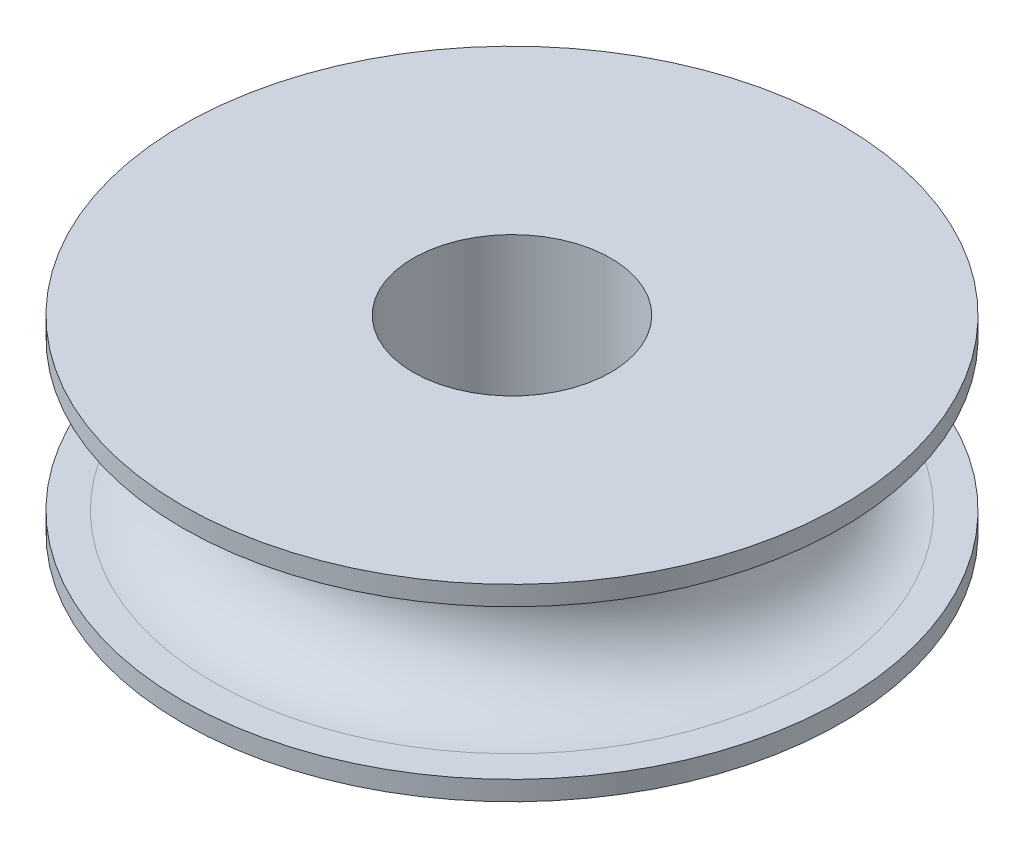
SolidWorks part; units mm, degrees
material "ABS PC"
ref_plane "Front Plane" through (0, 0, 0) normal (0, 0, 1) x (1, 0, 0)
ref_plane "Top Plane" through (0, 0, 0) normal (0, 1, 0) x (1, 0, 0)
ref_plane "Right Plane" through (0, 0, 0) normal (1, 0, 0) x (0, 0, -1)
sketch "Sketch1" plane through (0, 0, 0) normal (0, 0, 1) x (1, 0, 0)
  line L0 (0, 5.8882) -> (0, -5.8882) construction
  line L1 (-10.5, -3) -> (-5, -3)
  line L2 (-10.5, -3) -> (-10.5, -2.3812)
  line L3 (-10.5, -2.3812) -> (-9.5, -2.3813)
  line L4 (-9.5, 2.3812) -> (-10.5, 2.3813)
  line L5 (-10.5, 2.3813) -> (-10.5, 3)
  line L6 (-10.5, 3) -> (0, 3)
  line L7 (0, -5.5) -> (0, 3)
  line L12 (-5, -3) -> (-5, -5.5)
  line L13 (-5, -5.5) -> (0, -5.5)
  arc A0 (-9.5, 2.3812) -> (-9.5, -2.3813) centre (-9.5, 0) cw
  dimension "D3" = 9.5
  dimension "D5" = 2.3813
  dimension "D1" = 5.5
  dimension "D2" = 6
  dimension "D4" = 5
  dimension "D6" = 10.5
  dimension "D7" = 3
revolve "Revolve1" add sketch "Sketch1" angle 360 about L0
sketch "Sketch2" plane through (0, 3, 0) normal (0, 1, 0) x (1, 0, 0)
  circle A0 centre (0, 0) radius 3.15
  dimension "D1" = 6.3
extrude "Cut-Extrude1" cut sketch "Sketch2" against normal through all
ref_plane "Plane1" through (5, 0, 0) normal (1, 0, 0) x (0, 0, -1)
hole_wizard "M2x0.4 Tapped Hole2" positions "Sketch7" profile "Sketch8" tap size "M2x0.4" standard "ANSI Metric"
sketch "Sketch7" plane through (5, 0, 0) normal (1, 0, 0) x (0, 0, -1)
  line L0 (-5, -5.5) -> (5, -5.5) construction
  point P0 (0, -4.25)
  dimension "D1" = 1.25
sketch "Sketch8" plane through (5, -4.25, 0) normal (0, 1, 0) x (0, 0, -1)
  line L0 (0, 0) -> (0, 1.85)
  line L1 (0, 1.85) -> (0.8, 1.85)
  line L2 (0.8, 1.85) -> (0.8, 0)
  line L5 (0.8, 0) -> (0, 0)
  line L11 (0, -6.35) -> (0, 107.95) construction
  dimension "Thru Tap Drill Dia." = 1.6
  dimension "Thru Tap Drill Depth" = 1.85
cosmetic thread "Hole Thread1" parameters "D2"=2
